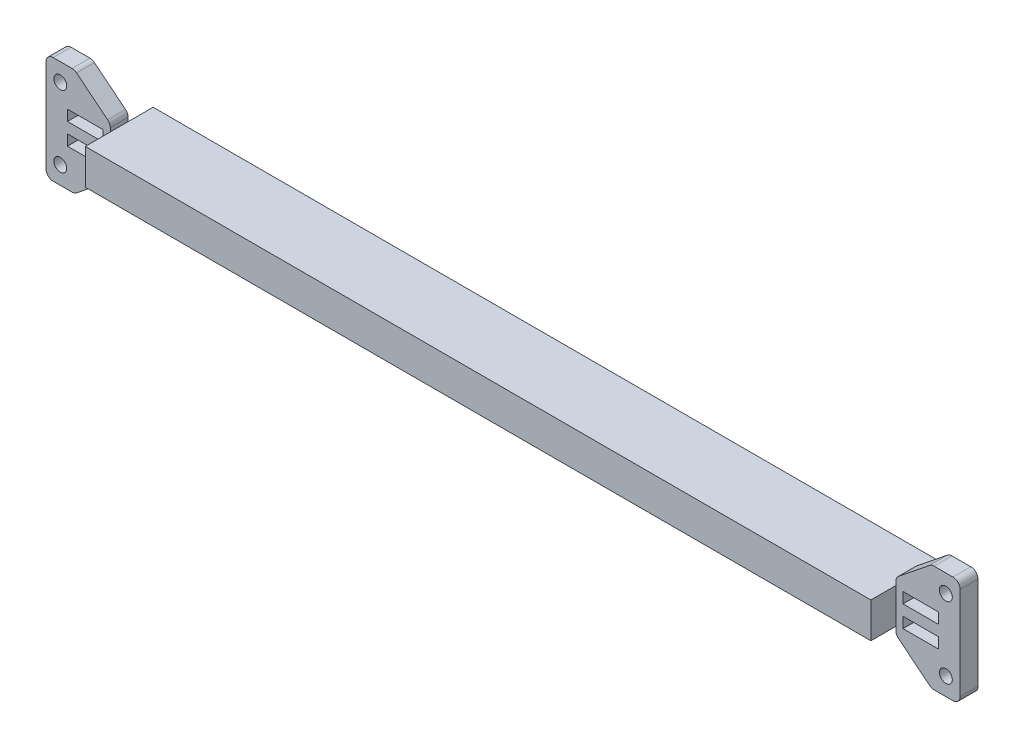
SolidWorks part; units mm, degrees
ref_plane "Front Plane" through (0, 0, 0) normal (0, 0, 1) x (1, 0, 0)
ref_plane "Top Plane" through (0, 0, 0) normal (0, 1, 0) x (1, 0, 0)
ref_plane "Right Plane" through (0, 0, 0) normal (1, 0, 0) x (0, 0, -1)
sketch "Sketch1" plane through (0, 0, 0) normal (0, 0, 1) x (1, 0, 0)
  line L1 (-139.7, -6.2865) -> (139.7, -6.2865)
  line L2 (-139.7, 6.2865) -> (139.7, 6.2865)
  line L7 (0, 6.2865) -> (0, -6.2865) construction
  line L13 (-139.7, -6.2865) -> (-139.7, -8.8265)
  line L15 (-152.4, 19.05) -> (-162.56, 19.05)
  line L16 (-139.7, 8.8265) -> (-139.7, 6.2865)
  line L17 (-152.4, -19.05) -> (-162.56, -19.05)
  line L18 (-162.56, 19.05) -> (-162.56, -19.05)
  line L19 (-154.94, 1.905) -> (-142.24, 1.905)
  line L20 (-154.94, 1.905) -> (-154.94, 5.715)
  line L21 (-154.94, 5.715) -> (-142.24, 5.715)
  line L22 (-142.24, 1.905) -> (-142.24, 5.715)
  line L26 (-139.7, -8.8265) -> (-152.4, -19.05)
  line L27 (-139.7, 8.8265) -> (-152.4, 19.05)
  line L28 (-162.56, 0) -> (0, 0) construction
  line L29 (-142.24, -1.905) -> (-142.24, -5.715)
  line L30 (-154.94, -5.715) -> (-142.24, -5.715)
  line L31 (-154.94, -1.905) -> (-142.24, -1.905)
  line L32 (-154.94, -1.905) -> (-154.94, -5.715)
  line L33 (154.94, -1.905) -> (154.94, -5.715)
  line L34 (154.94, -1.905) -> (142.24, -1.905)
  line L35 (154.94, -5.715) -> (142.24, -5.715)
  line L36 (142.24, -1.905) -> (142.24, -5.715)
  line L37 (139.7, 8.8265) -> (152.4, 19.05)
  line L38 (139.7, -8.8265) -> (152.4, -19.05)
  line L39 (142.24, 1.905) -> (142.24, 5.715)
  line L40 (154.94, 5.715) -> (142.24, 5.715)
  line L41 (154.94, 1.905) -> (154.94, 5.715)
  line L42 (154.94, 1.905) -> (142.24, 1.905)
  line L43 (162.56, 19.05) -> (162.56, -19.05)
  line L44 (152.4, -19.05) -> (162.56, -19.05)
  line L45 (139.7, 8.8265) -> (139.7, 6.2865)
  line L46 (152.4, 19.05) -> (162.56, 19.05)
  line L47 (139.7, -6.2865) -> (139.7, -8.8265)
  circle A6 centre (-157.48, -12.7) radius 2.286
  circle A8 centre (-157.48, 12.7) radius 2.286
  circle A9 centre (157.48, 12.7) radius 2.286
  circle A10 centre (157.48, -12.7) radius 2.286
  point P0 (0, 0)
  point P39 (-157.48, -19.05)
  point P41 (-162.56, 0)
  point P55 (162.56, 0)
  point P56 (157.48, -19.05)
  dimension "D3" = 139.7
  dimension "D9" = 38.1
  dimension "D10" = 4.572
  dimension "D2" = 1.905
  dimension "D4" = 12.7
  dimension "D7" = 12.573
  dimension "D11" = 5.08
  dimension "D12" = 3.81
  dimension "D13" = 12.7
  dimension "D14" = 7.62
  dimension "D15" = 2.54
  dimension "D16" = 10.16
  dimension "D17" = 22.86
extrude "Boss-Extrude1" add sketch "Sketch1" along normal mid plane 6.35
fillet "Fillet1" radius 2.54 12 edges at (139.7, 8.8265, 0) (152.4, 19.05, 0) (162.56, 19.05, 0) (162.56, -19.05, 0) (152.4, -19.05, 0) (139.7, -8.8265, 0) (-162.56, -19.05, 0) (-152.4, -19.05, 0) (-139.7, -8.8265, 0) (-139.7, 8.8265, 0) (-152.4, 19.05, 0) (-162.56, 19.05, 0)
sketch "Sketch3" plane through (0, 0, 3.175) normal (0, 0, 1) x (1, 0, 0)
  line L1 (-139.7, -6.2865) -> (139.7, -6.2865)
  line L2 (-139.7, -6.2865) -> (-139.7, 6.2865)
  line L3 (-139.7, 6.2865) -> (139.7, 6.2865)
  line L4 (139.7, -6.2865) -> (139.7, 6.2865)
  line L5 (-139.7, -6.2865) -> (139.7, 6.2865) construction
  line L6 (-139.7, 6.2865) -> (139.7, -6.2865) construction
  point P0 (0, 0)
extrude "Boss-Extrude3" add sketch "Sketch3" along normal blind 8.89
sketch "Sketch4" plane through (0, 0, 0) normal (0, 1, 0) x (1, 0, 0)
  line L1 (-154.94, -3.175) -> (-142.24, -3.175) construction
  line L2 (-148.59, -4.445) -> (-148.59, 3.175) construction
  line L3 (142.24, 3.175) -> (154.94, 3.175) construction
  line L4 (-142.24, 3.175) -> (-154.94, 3.175) construction
  circle A0 centre (-148.59, -4.445) radius 5.08
  dimension "D3" = 10.16
  dimension "D2" = 1.27
extrude "Cut-Extrude1" [suppressed] cut sketch "Sketch4" against normal mid plane 16.51
mirror "Mirror1" about plane through (0, 0, 0) normal (0, 0, 1) of "Boss-Extrude3"
sketch "Sketch5" plane through (0, 0, 0) normal (0, 1, 0) x (1, 0, 0)
  line L0 (148.59, 4.445) -> (148.59, -3.175) construction
  line L1 (154.94, -3.175) -> (142.24, -3.175) construction
  line L2 (142.24, -3.175) -> (154.94, -3.175) construction
  circle A0 centre (148.59, 4.445) radius 5.08
  dimension "D1" = 10.16
  dimension "D2" = 7.62
extrude "Cut-Extrude2" [suppressed] cut sketch "Sketch5" against normal mid plane 16.51
